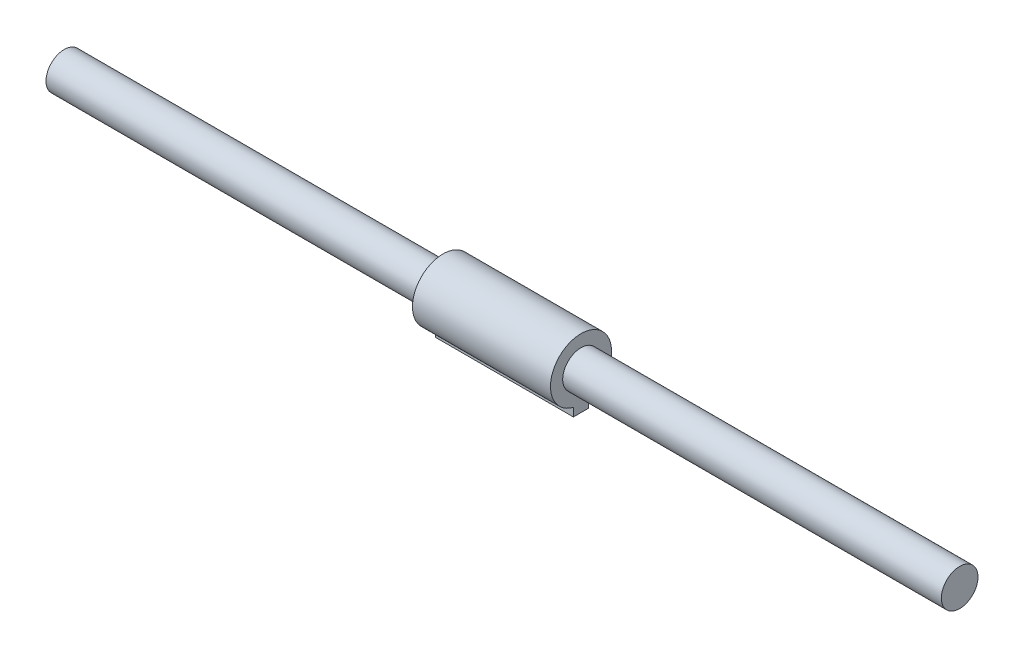
SolidWorks part; units mm, degrees
ref_plane "Front Plane" through (0, 0, 0) normal (0, 0, 1) x (1, 0, 0)
ref_plane "Top Plane" through (0, 0, 0) normal (0, 1, 0) x (1, 0, 0)
ref_plane "Right Plane" through (0, 0, 0) normal (1, 0, 0) x (0, 0, -1)
sketch "Sketch1" plane through (0, 0, 0) normal (1, 0, 0) x (0, 0, -1)
  line L1 (1.5875, -6.1484) -> (1.5875, -7.873)
  line L2 (1.5875, -7.873) -> (-1.5875, -7.873)
  line L3 (-1.5875, -7.873) -> (-1.5875, -6.1484)
  arc A0 (1.5875, -6.1484) -> (-1.5875, -6.1484) centre (0, 0) ccw
  dimension "D1" = 12.7
  dimension "D3" = 1.7247
  dimension "D2" = 3.175
extrude "Boss-Extrude1" add sketch "Sketch1" along normal blind 28.702
sketch "Sketch3" plane through (28.702, 0, 0) normal (1, 0, 0) x (0, 0, -1)
  circle A0 centre (0, 0) radius 3.81
  dimension "D1" = 7.62
extrude "Boss-Extrude3" add sketch "Sketch3" along normal blind 78.74
sketch "Sketch4" plane through (0, 0, 0) normal (-1, 0, 0) x (0, 0, 1)
  circle A0 centre (0, 0) radius 3.81
  dimension "D1" = 7.62
extrude "Boss-Extrude4" add sketch "Sketch4" along normal blind 78.74
